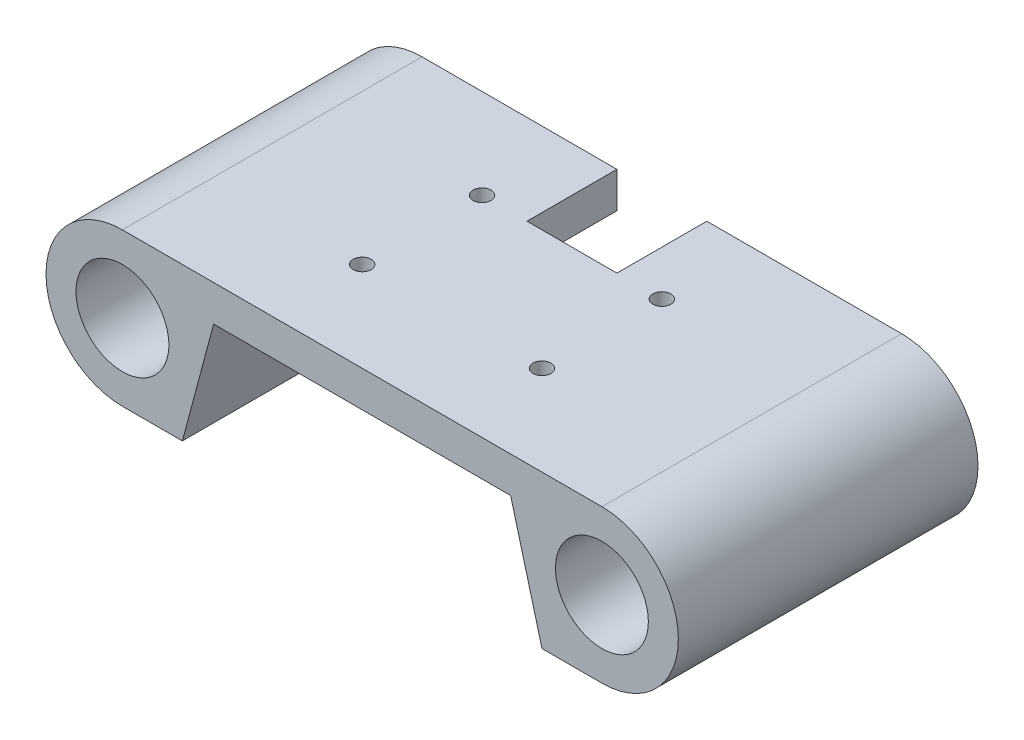
SolidWorks part; units mm, degrees
material "ABS"
ref_plane "Plano frontal" through (0, 0, 0) normal (0, 0, 1) x (1, 0, 0)
ref_plane "Plano superior" through (0, 0, 0) normal (0, 1, 0) x (1, 0, 0)
ref_plane "Plano direito" through (0, 0, 0) normal (1, 0, 0) x (0, 0, -1)
sketch "Esboço1" plane through (0, 0, 0) normal (0, 0, 1) x (1, 0, 0)
  line L0 (40, 0) -> (-40, 0)
  line L2 (-40, -25.499) -> (-30, -25.499)
  line L3 (-30, -25.499) -> (-24.7752, -6)
  line L6 (0, 0) -> (0, -46.1263) construction
  line L8 (30, -25.499) -> (24.7752, -6)
  line L9 (40, -25.499) -> (30, -25.499)
  line L11 (-24.7752, -6) -> (24.7752, -6)
  line L12 (-40, -12.7495) -> (40, -12.7495) construction
  circle A0 centre (-40, -12.7495) radius 7.75
  circle A1 centre (40, -12.7495) radius 7.75
  arc A2 (40, -25.499) -> (40, 0) centre (40, -12.7495) ccw
  arc A3 (-40, 0) -> (-40, -25.499) centre (-40, -12.7495) ccw
  point P17 (0, -12.2866)
  dimension "D1" = 15.5
  dimension "D10" = 12.7495
  dimension "D3" = 75
  dimension "D4" = 10
  dimension "D5" = 6
  dimension "D6" = 40
extrude "Ressalto-extrusão1" add sketch "Esboço1" along normal blind 50
sketch "Esboço2" plane through (0, -25.499, 0) normal (0, -1, 0) x (1, 0, 0)
  line L0 (15, 35) -> (15, 15) construction
  line L1 (-52.7495, 25) -> (52.7495, 25) construction
  line L2 (-52.7495, 50) -> (-52.7495, 0) construction
  line L3 (52.7495, 0) -> (52.7495, 50) construction
  line L6 (0, 0) -> (0, 50) construction
  line L7 (-24.7752, 50) -> (24.7752, 50) construction
  line L8 (-15, 35) -> (-15, 15) construction
  line L9 (-24.7752, 0) -> (24.7752, 0) construction
  line L10 (-7.5, 15) -> (7.5, 15)
  line L11 (-7.5, 15) -> (-7.5, 0)
  line L12 (-7.5, 0) -> (7.5, 0)
  line L13 (7.5, 15) -> (7.5, 0)
  line L14 (-7.5, 15) -> (7.5, 0) construction
  line L15 (-7.5, 0) -> (7.5, 15) construction
  circle A0 centre (15, 35) radius 1.5
  circle A1 centre (15, 15) radius 1.5
  circle A2 centre (-15, 15) radius 1.5
  circle A3 centre (-15, 35) radius 1.5
  point P10 (15, 25)
  point P20 (0, 7.5)
  dimension "D1" = 20
  dimension "D2" = 3
  dimension "D3" = 15
  dimension "D4" = 15
  dimension "D5" = 15
extrude "Corte-extrusão1" cut sketch "Esboço2" against normal blind 30
